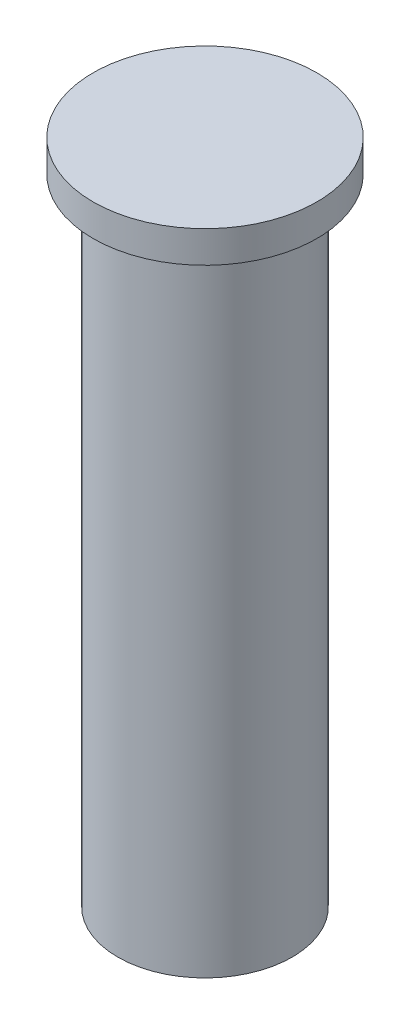
SolidWorks part; units mm, degrees
ref_plane "Front Plane" through (0, 0, 0) normal (0, 0, 1) x (1, 0, 0)
ref_plane "Top Plane" through (0, 0, 0) normal (0, 1, 0) x (1, 0, 0)
ref_plane "Right Plane" through (0, 0, 0) normal (1, 0, 0) x (0, 0, -1)
sketch "Sketch2" plane through (0, 0, 0) normal (0, 1, 0) x (1, 0, 0)
  circle A0 centre (0, 0) radius 6.985
  dimension "D1" = 13.97
extrude "Boss-Extrude1" add sketch "Sketch2" along normal blind 50.8
sketch "Sketch3" plane through (0, 50.8, 0) normal (0, 1, 0) x (1, 0, 0)
  circle A0 centre (0, 0) radius 8.9569
extrude "Boss-Extrude2" add sketch "Sketch3" along normal blind 2.54
